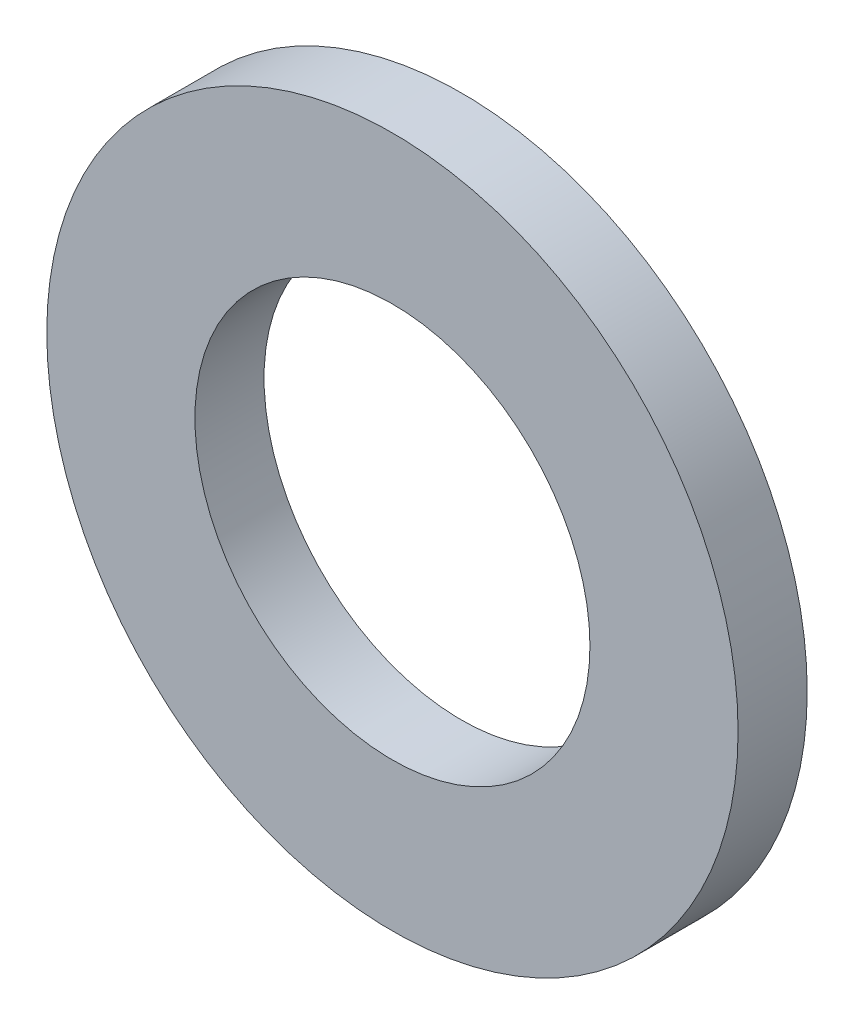
SolidWorks part; units mm, degrees
material "铸造不锈钢"
ref_plane "前视基准面" through (0, 0, 0) normal (0, 0, 1) x (1, 0, 0)
ref_plane "上视基准面" through (0, 0, 0) normal (0, 1, 0) x (1, 0, 0)
ref_plane "右视基准面" through (0, 0, 0) normal (1, 0, 0) x (0, 0, -1)
other "Configuration Table"
sketch "草图1" plane through (0, 0, 0) normal (0, 0, 1) x (1, 0, 0)
  circle A0 centre (0, 0) radius 2
  circle A1 centre (0, 0) radius 3.5
  dimension "D1" = 7
  dimension "D2" = 4
extrude "凸台-拉伸1" add sketch "草图1" along normal blind 0.7
